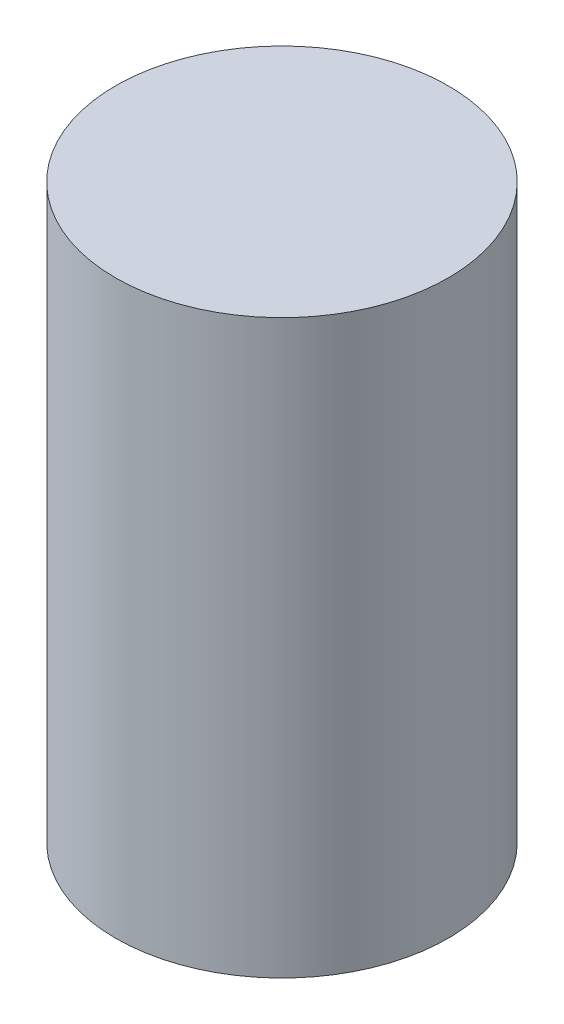
SolidWorks part; units mm, degrees
ref_plane "Front Plane" through (0, 0, 0) normal (0, 0, 1) x (1, 0, 0)
ref_plane "Top Plane" through (0, 0, 0) normal (0, 1, 0) x (1, 0, 0)
ref_plane "Right Plane" through (0, 0, 0) normal (1, 0, 0) x (0, 0, -1)
sketch "Sketch1" plane through (0, 0, 0) normal (0, 1, 0) x (1, 0, 0)
  circle A0 centre (0, 0) radius 4
  dimension "D1" = 8
extrude "Boss-Extrude1" add sketch "Sketch1" along normal blind 13.75
